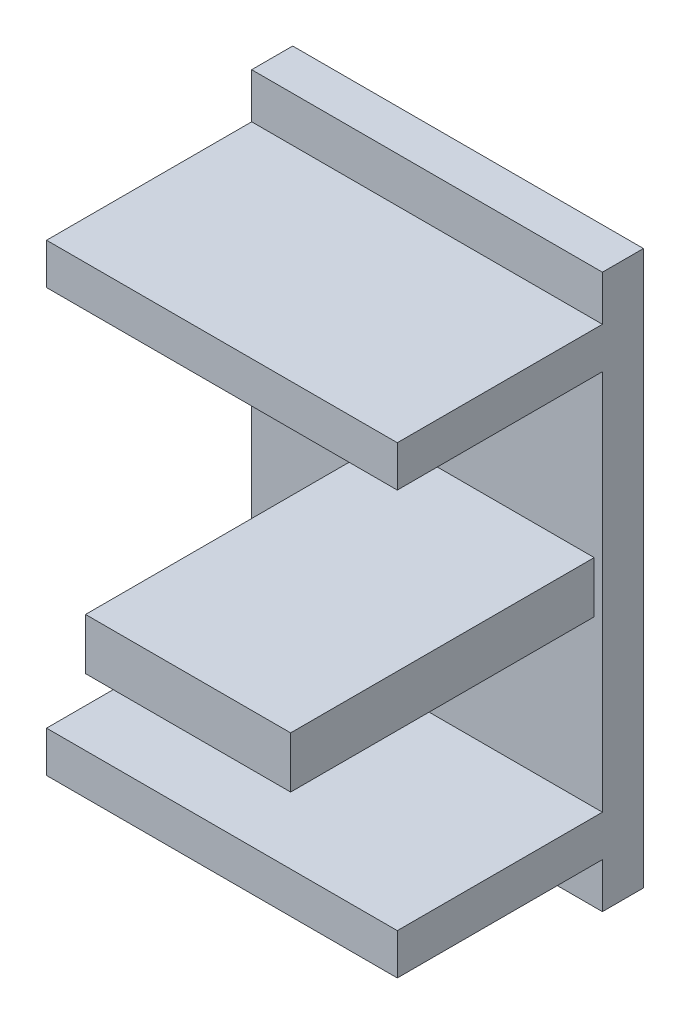
SolidWorks part; units mm, degrees
ref_plane "Front Plane" through (0, 0, 0) normal (1, 0, 0) x (0, 1, 0)
ref_plane "Top Plane" through (0, 0, 0) normal (0, 0, 1) x (0, 1, 0)
ref_plane "Right Plane" through (0, 0, 0) normal (0, 1, 0) x (-1, 0, 0)
sketch "Sketch1" plane through (0, 0, 0) normal (0, 0, 1) x (0, 1, 0)
  line L1 (0, 0) -> (68.58, 0)
  line L2 (0, 0) -> (0, 43.434)
  line L3 (0, 43.434) -> (68.58, 43.434)
  line L4 (68.58, 0) -> (68.58, 43.434)
  dimension "D1" = 68.58
  dimension "D2" = 43.434
extrude "Boss-Extrude1" add sketch "Sketch1" along normal blind 5.08
sketch "Sketch2" plane through (0, 0, 5.08) normal (0, 0, 1) x (1, 0, 0)
  line L0 (-43.434, 68.58) -> (-43.434, 0) construction
  line L1 (-43.434, 5.588) -> (0, 5.588)
  line L2 (-43.434, 5.588) -> (-43.434, 10.668)
  line L3 (-43.434, 10.668) -> (0, 10.668)
  line L4 (0, 5.588) -> (0, 10.668)
  line L5 (0, 0) -> (0, 68.58) construction
  line L6 (-43.434, 0) -> (0, 0) construction
  line L7 (-43.434, 57.912) -> (0, 57.912)
  line L8 (-43.434, 57.912) -> (-43.434, 62.992)
  line L9 (-43.434, 62.992) -> (0, 62.992)
  line L10 (0, 57.912) -> (0, 62.992)
  line L11 (0, 68.58) -> (-43.434, 68.58) construction
  dimension "D1" = 5.08
  dimension "D2" = 5.08
  dimension "D3" = 5.588
  dimension "D4" = 5.588
extrude "Boss-Extrude2" add sketch "Sketch2" along normal blind 25.4
sketch "Sketch3" plane through (0, 0, 5.08) normal (0, 0, 1) x (1, 0, 0)
  line L0 (-13.716, 37.465) -> (-13.716, 31.115) construction
  line L1 (-26.416, 31.115) -> (-1.016, 31.115)
  line L2 (-26.416, 31.115) -> (-26.416, 37.465)
  line L3 (-26.416, 37.465) -> (-1.016, 37.465)
  line L4 (-1.016, 31.115) -> (-1.016, 37.465)
  line L6 (-43.434, 57.912) -> (-43.434, 10.668) construction
  line L7 (-22.7288, 10.668) -> (-22.7288, 57.912) construction
  line L8 (0, 10.668) -> (-43.434, 10.668) construction
  line L9 (-43.434, 57.912) -> (0, 57.912) construction
  point P14 (-22.7288, 34.29)
  point P15 (-13.716, 34.29)
  dimension "D1" = 29.718
  dimension "D2" = 6.35
  dimension "D3" = 25.4
extrude "Boss-Extrude3" add sketch "Sketch3" along normal blind 37.592
